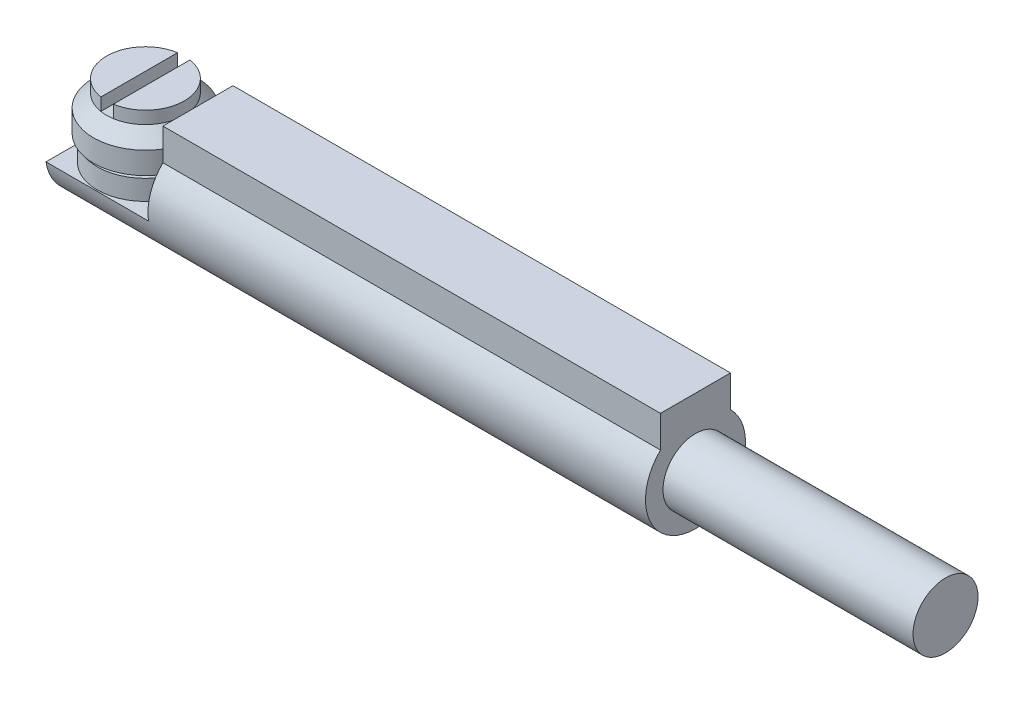
SolidWorks part; units mm, degrees
ref_plane "Front" through (0, 0, 0) normal (0, 0, 1) x (1, 0, 0)
ref_plane "Top" through (0, 0, 0) normal (0, 1, 0) x (1, 0, 0)
ref_plane "Right" through (0, 0, 0) normal (1, 0, 0) x (0, 0, -1)
sketch "Sketch1" plane through (0, 0, 0) normal (1, 0, 0) x (0, 0, -1)
  line L0 (0, -1.3742) -> (0, 2.1249) construction
  line L1 (-1.4, 2.7) -> (1.4, 2.7)
  line L2 (-1.4, 2.7) -> (-1.4, 1.4283)
  line L4 (1.4, 2.7) -> (1.4, 1.4283)
  arc A0 (-1.4, 1.4283) -> (1.4, 1.4283) centre (0, 0) ccw
  dimension "D1" = 4
  dimension "D2" = 2.8
  dimension "D3" = 2.7
extrude "Boss-Extrude1" add sketch "Sketch1" along normal blind 24
sketch "Sketch2" plane through (0, 2.7, 0) normal (0, 1, 0) x (1, 0, 0)
  line L1 (-4.1, 2.5) -> (4.1, 2.5)
  line L2 (-4.1, 2.5) -> (-4.1, -2.5)
  line L3 (-4.1, -2.5) -> (4.1, -2.5)
  line L4 (4.1, 2.5) -> (4.1, -2.5)
  line L5 (-4.1, 2.5) -> (4.1, -2.5) construction
  line L6 (-4.1, -2.5) -> (4.1, 2.5) construction
  point P0 (0, 0)
  dimension "D1" = 4.1
  dimension "D2" = 5
extrude "Cut-Extrude1" cut sketch "Sketch2" against normal blind 3
sketch "Sketch3" plane through (0, 0, 0) normal (0, 0, 1) x (1, 0, 0)
  line L0 (0.075, 0.5) -> (1.225, 0.5)
  line L1 (2, -0.3) -> (2, 2.6)
  line L2 (1.225, 0.7) -> (-0.075, 0.7)
  line L3 (0.445, 2.6) -> (0.445, 2.1)
  line L5 (2, 2.6) -> (0.445, 2.6)
  line L7 (2, 2.6) -> (2, -0.3) construction
  line L8 (1.225, 0.7) -> (1.225, 0.5)
  line L13 (0.075, 0.5) -> (0.075, -0.3)
  line L14 (0.075, -0.3) -> (2, -0.3)
  line L15 (-0.075, 1.58) -> (-0.075, 0.7)
  line L16 (0.445, 2.1) -> (-0.075, 1.58)
  dimension "D1" = 1.555
  dimension "D2" = 2.075
  dimension "D3" = 0.775
  dimension "D4" = 1.925
  dimension "D5" = 0.8
  dimension "D6" = 1
  dimension "D7" = 1.88
  dimension "D8" = 2.9
  dimension "D9" = 45
  dimension "D10" = 2
  dimension "D11" = 0.3
revolve "Revolve1" add sketch "Sketch3" angle 360 about L7
sketch "Sketch4" plane through (0, 2.6, 0) normal (0, 1, 0) x (1, 0, 0)
  line L0 (2, 4.3917) -> (2, -3.4879) construction
  line L1 (1.75, 2.5) -> (2.25, 2.5)
  line L2 (1.75, 2.5) -> (1.75, -2.5)
  line L3 (1.75, -2.5) -> (2.25, -2.5)
  line L4 (2.25, 2.5) -> (2.25, -2.5)
  line L5 (1.75, 2.5) -> (2.25, -2.5) construction
  line L6 (1.75, -2.5) -> (2.25, 2.5) construction
  line L8 (-1.4304, 0) -> (4.856, 0) construction
  point P0 (2, 0)
  dimension "D1" = 0.5
  dimension "D2" = 2
  dimension "D3" = 5
extrude "Cut-Extrude2" cut sketch "Sketch4" against normal blind 0.5
sketch "Sketch5" plane through (24, 0, 0) normal (1, 0, 0) x (0, 0, -1)
  circle A0 centre (0, 0) radius 1.3
  dimension "D1" = 2.6
extrude "Boss-Extrude2" add sketch "Sketch5" along normal blind 10
